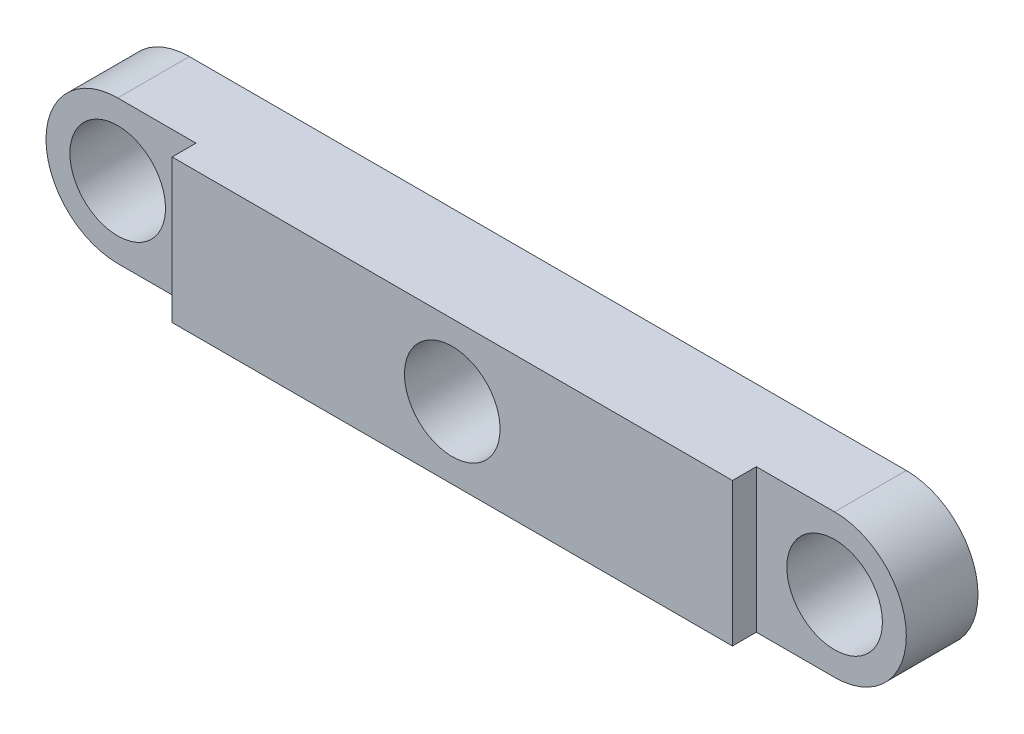
SolidWorks part; units mm, degrees
ref_plane "Спереди" through (0, 0, 0) normal (0, 0, 1) x (1, 0, 0)
ref_plane "Сверху" through (0, 0, 0) normal (0, 1, 0) x (1, 0, 0)
ref_plane "Справа" through (0, 0, 0) normal (1, 0, 0) x (0, 0, -1)
other "Configuration Table"
sketch "Эскиз1" plane through (0, 0, 0) normal (0, 0, 1) x (1, 0, 0)
  line L0 (-75, 0) -> (0, 0) construction
  line L1 (0, 0) -> (75, 0) construction
  line L2 (-75, 0) -> (75, 0) construction
  line L3 (-75, 15) -> (75, 15)
  line L4 (-75, -15) -> (75, -15)
  circle A0 centre (-75, 0) radius 10
  circle A1 centre (0, 0) radius 10
  circle A2 centre (75, 0) radius 10
  arc A3 (-75, 15) -> (-75, -15) centre (-75, 0) ccw
  arc A4 (75, -15) -> (75, 15) centre (75, 0) ccw
  point P7 (0, 0)
  dimension "D1" = 20
  dimension "D2" = 150
  dimension "D3" = 30
extrude "Бобышка-Вытянуть1" add sketch "Эскиз1" along normal mid plane 20
sketch "Эскиз2" plane through (0, 0, 10) normal (0, 0, 1) x (1, 0, 0)
  line L0 (-58.6201, 15) -> (-58.6201, -15)
  line L1 (75, 15) -> (-75, 15) construction
  line L2 (-75, -15) -> (75, -15) construction
  line L3 (-58.6201, -15) -> (-93.8799, -15)
  line L4 (-93.8799, -15) -> (-93.8799, 15)
  line L5 (-93.8799, 15) -> (-58.6201, 15)
  line L6 (-75, 0) -> (-58.6201, 0) construction
  line L7 (58.6201, 15) -> (58.6201, -15)
  line L8 (58.6201, -15) -> (93.8799, -15)
  line L9 (93.8799, -15) -> (93.8799, 15)
  line L10 (93.8799, 15) -> (58.6201, 15)
  line L11 (75, 0) -> (58.6201, 0) construction
  dimension "D1" = 18.8799
  dimension "D2" = 16.3799
extrude "Вырез-Вытянуть1" cut sketch "Эскиз2" against normal blind 5
